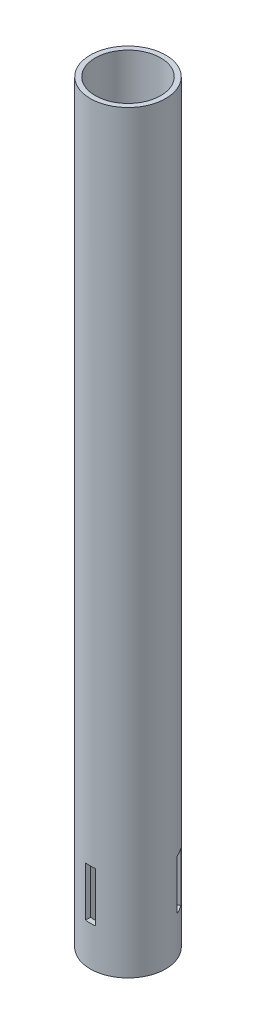
SolidWorks part; units mm, degrees
ref_plane "Front Plane" through (0, 0, 0) normal (0, 0, 1) x (1, 0, 0)
ref_plane "Top Plane" through (0, 0, 0) normal (0, 1, 0) x (1, 0, 0)
ref_plane "Right Plane" through (0, 0, 0) normal (1, 0, 0) x (0, 0, -1)
sketch "Sketch1" plane through (0, 0, 0) normal (0, 1, 0) x (1, 0, 0)
  circle A0 centre (0, 0) radius 3.8
  circle A1 centre (0, 0) radius 3.3
  dimension "D1" = 7.6
  dimension "D2" = 0.5
extrude "Boss-Extrude2" add sketch "Sketch1" along normal blind 76 contours A1
sketch "Sketch2" plane through (0, 0, 0) normal (0, 0, 1) x (1, 0, 0)
  line L0 (0, 0) -> (0, 20.4478)
  line L1 (0.55, 0) -> (-0.55, 0) construction
  line L2 (-0.5, 4) -> (0.5, 4)
  line L3 (-0.5, 4) -> (-0.5, 9)
  line L4 (-0.5, 9) -> (0.5, 9)
  line L5 (0.5, 4) -> (0.5, 9)
  line L6 (-0.5, 4) -> (0.5, 9) construction
  line L7 (-0.5, 9) -> (0.5, 4) construction
  point P3 (0, 6.5)
  dimension "D1" = 5
  dimension "D2" = 1
  dimension "D3" = 4
extrude "Cut-Extrude4" cut sketch "Sketch2" along normal blind 8 contours L5 L4 L3 L2
pattern_circular "CirPattern1" count 3 over 360 about axis through (0, 0, 0) along (0, 1, 0) of "Cut-Extrude4"
